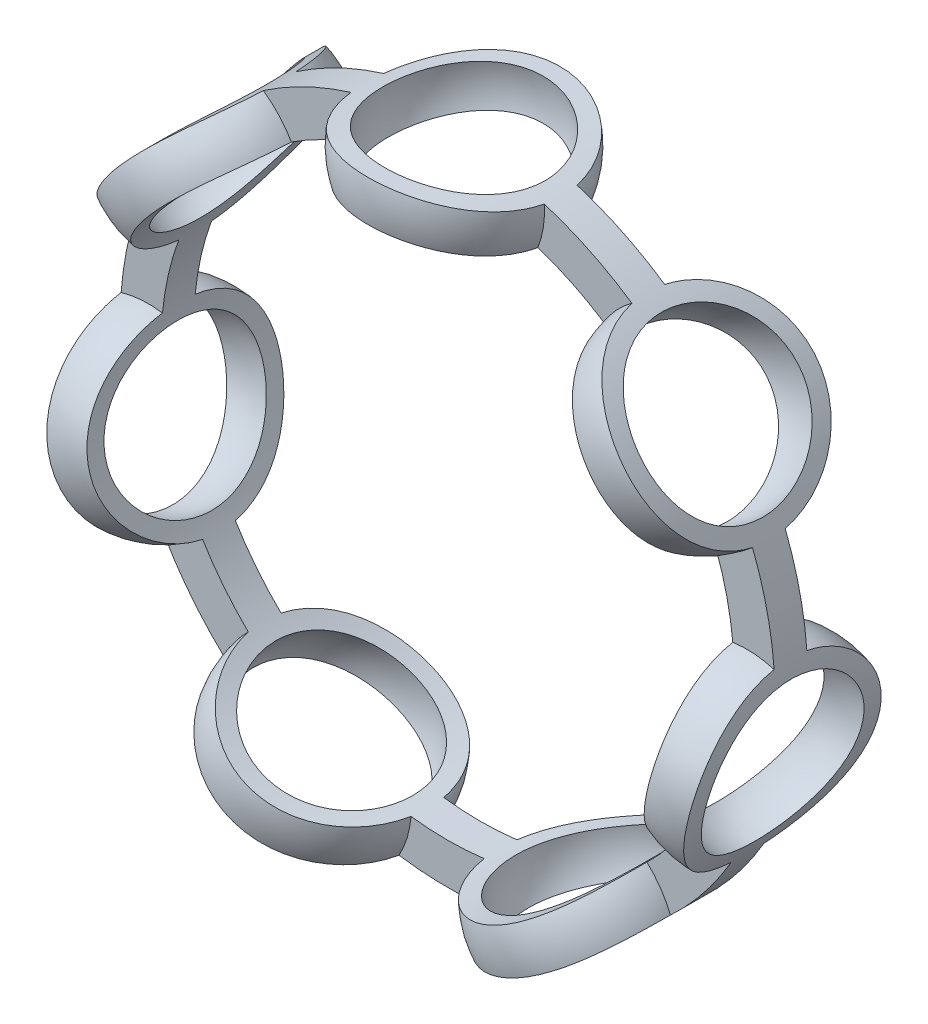
SolidWorks part; units mm, degrees
ref_plane "Plan1" through (0, 0, 0) normal (0, 0, 1) x (1, 0, 0)
ref_plane "Plan2" through (0, 0, 0) normal (0, 1, 0) x (1, 0, 0)
ref_plane "Plan3" through (0, 0, 0) normal (1, 0, 0) x (0, 0, -1)
sketch "Esquisse1" plane through (0, 0, 0) normal (0, 0, 1) x (1, 0, 0)
  circle A0 centre (0, 0) radius 7.5
  dimension "D1" = 15
extrude "Base-Extru.-Mince" add sketch "Esquisse1" along normal mid plane 0.8 thin thin type mid plane wall 1
sketch "Esquisse2" plane through (0, 0, 0) normal (0, 0, 1) x (1, 0, 0)
  line L0 (0, 1.0573) -> (0, 12.0999) construction
  line L2 (0, 9.9) -> (0, 5.1)
  arc A1 (0, 9.9) -> (0, 5.1) centre (0, 7.5) ccw
  dimension "D2" = 2.4
  dimension "D1" = 7.5
revolve "Boss.-Révol.1" add sketch "Esquisse2" angle 360 about L0
sketch "Esquisse3" plane through (0, 0, 0) normal (0, 0, 1) x (1, 0, 0)
  line L0 (0, 12.2917) -> (0, 1.0573) construction
  line L1 (0, 1.0573) -> (0, 12.0999) construction
  line L2 (0, 5.5) -> (0, 9.5)
  arc A0 (0, 9.5) -> (0, 5.5) centre (0, 7.5) ccw
  arc A1 (2.3963, 7.6327) -> (-2.3963, 7.6327) centre (0, 7.5) ccw construction
  dimension "D1" = 2
revolve "Enlèvement de matière-Révolution2" cut sketch "Esquisse3" angle 360 about L0
pattern_circular "Répétition circulaire1" count 7 over 360 about axis through (0, 0, 0) along (0, 0, 1) of "Enlèvement de matière-Révolution2", "Boss.-Révol.1"
sketch "Esquisse4" plane through (0, 0, 0) normal (0, 0, 1) x (1, 0, 0)
  circle A0 centre (0, 0) radius 7
  circle A1 centre (0, 0) radius 8
  dimension "D1" = 14
  dimension "D2" = 16
extrude "Enlèv. mat.-Extru.1" cut sketch "Esquisse4" against normal mid plane 10 flip side to cut
